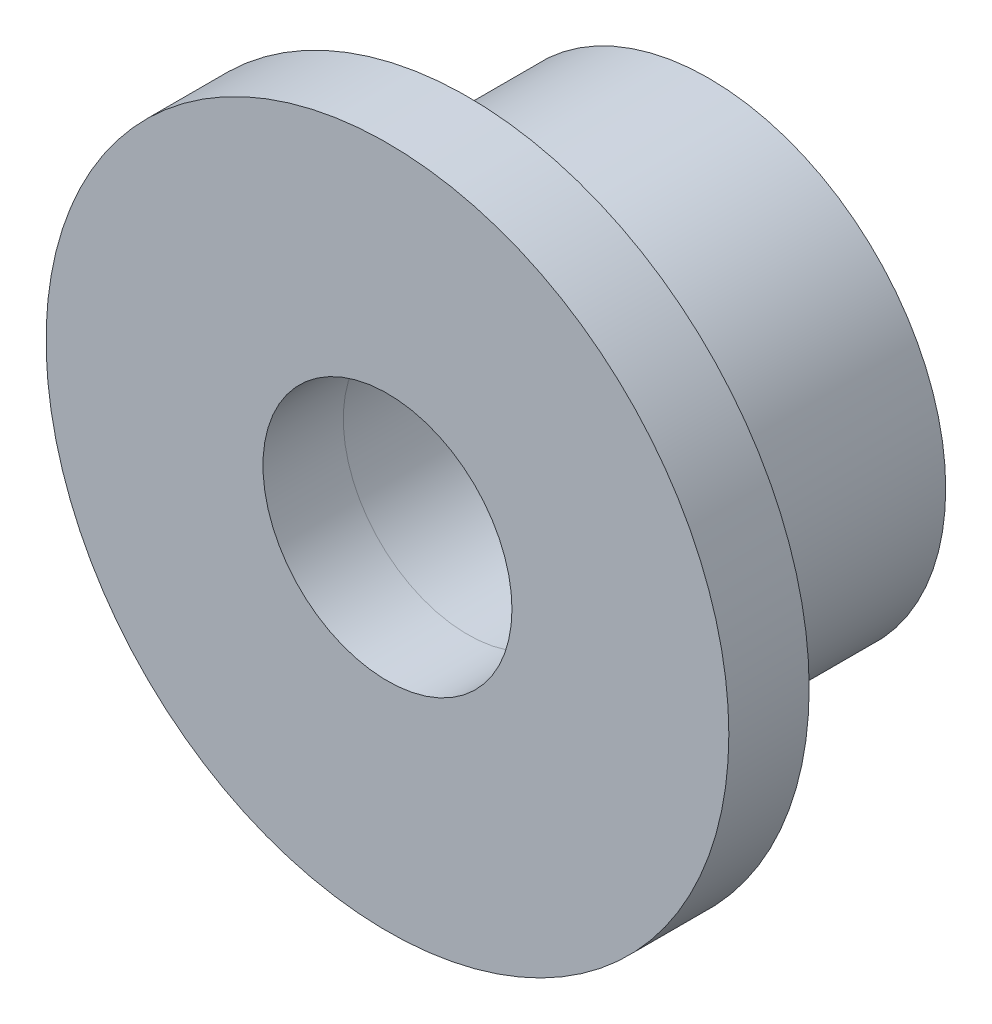
SolidWorks part; units mm, degrees
ref_plane "Alzado" through (0, 0, 0) normal (0, 0, 1) x (1, 0, 0)
ref_plane "Planta" through (0, 0, 0) normal (0, 1, 0) x (1, 0, 0)
ref_plane "Vista lateral" through (0, 0, 0) normal (1, 0, 0) x (0, 0, -1)
sketch "Croquis1" plane through (0, 0, 0) normal (0, 0, 1) x (1, 0, 0)
  circle A0 centre (0, 0) radius 2.95
  circle A1 centre (0, 0) radius 1.55
  dimension "D1" = 5.9
  dimension "D2" = 3.1
extrude "Saliente-Extruir1" add sketch "Croquis1" along normal blind 3
sketch "Croquis2" plane through (0, 0, 3) normal (0, 0, 1) x (1, 0, 0)
  circle A0 centre (0, 0) radius 4.25
  circle A1 centre (0, 0) radius 1.55
  dimension "D1" = 8.5
  dimension "D2" = 3.1
extrude "Saliente-Extruir2" add sketch "Croquis2" along normal blind 1 separate body
